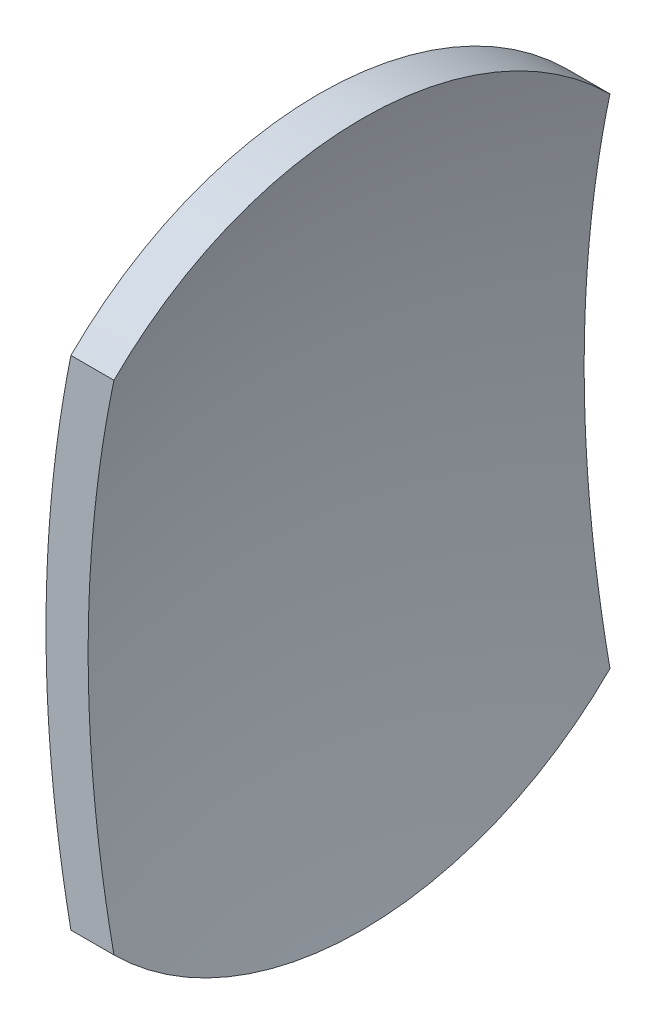
SolidWorks part; units mm, degrees
ref_plane "前视基准面" through (0, 0, 0) normal (0, 0, 1) x (1, 0, 0)
ref_plane "上视基准面" through (0, 0, 0) normal (0, 1, 0) x (1, 0, 0)
ref_plane "右视基准面" through (0, 0, 0) normal (1, 0, 0) x (0, 0, -1)
other "Configuration Table"
sketch "草图2" plane through (0, 0, 0) normal (0, 0, 1) x (1, 0, 0)
  line L0 (0, 0) -> (-60, 0) construction
  line L1 (-59.6238, 17) -> (-57.5413, 17)
  line L2 (-60, 0) -> (-62, 0)
  arc A0 (-57.5413, 17) -> (-60, 0) centre (0, 0) ccw
  arc A1 (-59.6238, 17) -> (-62, 0) centre (0, 0) ccw
  dimension "D1" = 120
  dimension "D2" = 2
  dimension "D3" = 17
revolve "旋转1" add sketch "草图2" angle 360 about L0
sketch "草图3" plane through (0, 0, 0) normal (1, 0, 0) x (0, 0, -1)
  line L0 (-12, 12.0416) -> (-12, -12.0416)
  line L1 (12, 12.0416) -> (12, -12.0416)
  circle A0 centre (0, 0) radius 17 construction
  arc A1 (12, -12.0416) -> (12, 12.0416) centre (0, 0) ccw
  circle A2 centre (0, 0) radius 17
  arc A3 (-12, 12.0416) -> (-12, -12.0416) centre (0, 0) ccw
  dimension "D1" = 0
  dimension "D2" = 12
  dimension "D3" = 12
extrude "切除-拉伸1" cut sketch "草图3" against normal up to next
sketch "草图4" plane through (0, 0, 0) normal (0, 1, 0) x (1, 0, 0)
  line L0 (0, 0) -> (-60, 0) construction
  line L1 (0, -20) -> (0, 20) construction
  line L2 (0, 20) -> (-60, 12) construction
  line L3 (-60, 12) -> (-60, -12) construction
  line L5 (-59.6238, 12) -> (-57.5413, 12) construction
  line L6 (0, -20) -> (-60, -12) construction
  point P4 (-60.2257, 12)
  dimension "D1" = 60
  dimension "D2" = 20
sketch "草图5" plane through (0, 0, 0) normal (0, 0, 1) x (1, 0, 0)
  line L0 (-60, -17) -> (-60, 17) construction
  line L1 (0, 0) -> (-60, 0) construction
  line L2 (-60, 17) -> (0, 20) construction
  line L3 (0, 20) -> (0, -20) construction
  line L4 (-57.5413, 17) -> (-59.6238, 17) construction
  line L5 (-60, 0) -> (0, 0) construction
  line L6 (-60, -17) -> (0, -20) construction
  dimension "D1" = 20
